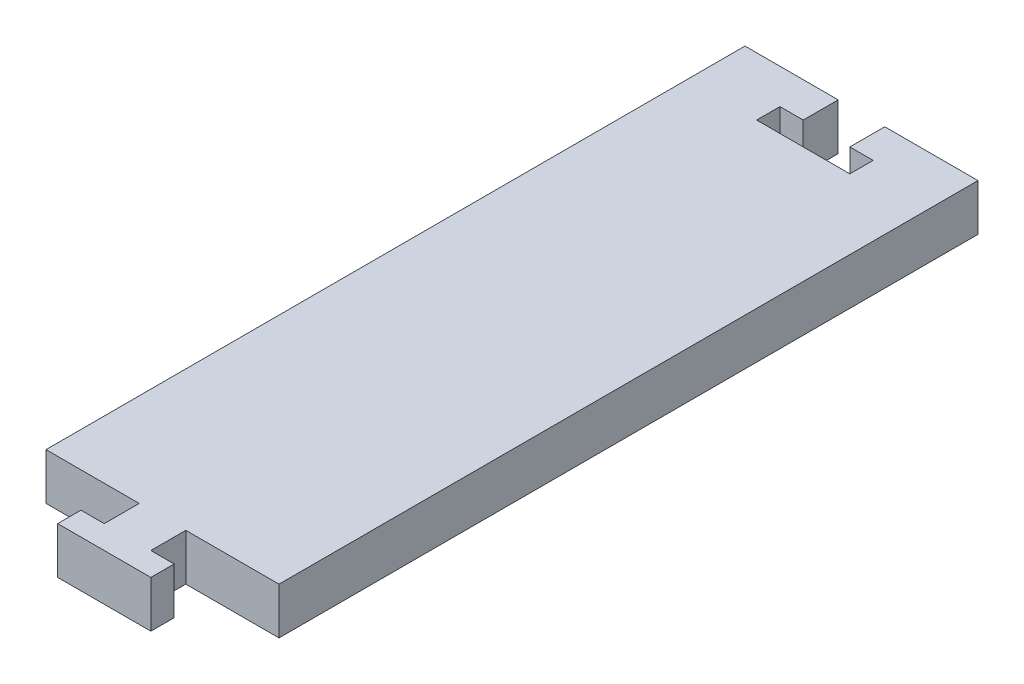
SolidWorks part; units mm, degrees
ref_plane "Спереди" through (0, 0, 0) normal (0, 0, 1) x (1, 0, 0)
ref_plane "Сверху" through (0, 0, 0) normal (0, 1, 0) x (1, 0, 0)
ref_plane "Справа" through (0, 0, 0) normal (1, 0, 0) x (0, 0, -1)
sketch "Эскиз1" plane through (0, 0, 0) normal (0, 1, 0) x (1, 0, 0)
  line L0 (0, 0) -> (0, -22.5) construction
  line L1 (10, -17.5) -> (2, -17.5)
  line L2 (10, -17.5) -> (10, 42.5)
  line L3 (-10, 42.5) -> (10, 42.5) construction
  line L4 (-10, -17.5) -> (-10, 42.5)
  line L5 (-4, -22.5) -> (4, -22.5)
  line L6 (4, -22.5) -> (4, -20.5)
  line L7 (4, -20.5) -> (2, -20.5)
  line L8 (2, -20.5) -> (2, -17.5)
  line L9 (-4, -22.5) -> (-4, -20.5)
  line L10 (-4, -20.5) -> (-2, -20.5)
  line L11 (-2, -20.5) -> (-2, -17.5)
  line L12 (-2, -17.5) -> (-10, -17.5)
  line L13 (-2, 42.5) -> (-10, 42.5)
  line L14 (-4, 37.5) -> (4, 37.5)
  line L15 (4, 37.5) -> (4, 39.5)
  line L16 (4, 39.5) -> (2, 39.5)
  line L17 (2, 39.5) -> (2, 42.5)
  line L18 (-4, 37.5) -> (-4, 39.5)
  line L19 (-4, 39.5) -> (-2, 39.5)
  line L20 (-2, 39.5) -> (-2, 42.5)
  line L21 (10, 42.5) -> (2, 42.5)
  point P0 (0, 0)
  point P6 (-10, 42.5)
  dimension "D1" = 3
  dimension "D2" = 20
  dimension "D3" = 60
  dimension "D5" = 4
  dimension "D6" = 2
  dimension "D7" = 2
  dimension "D9" = 4
extrude "Бобышка-Вытянуть1" add sketch "Эскиз1" along normal blind 4
